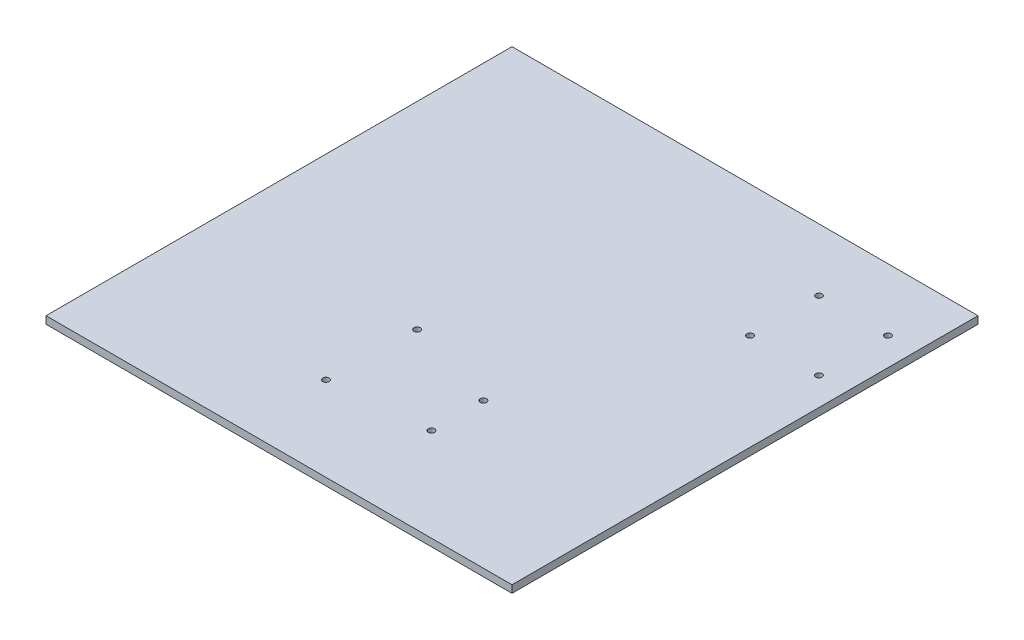
SolidWorks part; units mm, degrees
ref_plane "Front Plane" through (0, 0, 0) normal (0, 0, 1) x (1, 0, 0)
ref_plane "Top Plane" through (0, 0, 0) normal (0, 1, 0) x (1, 0, 0)
ref_plane "Right Plane" through (0, 0, 0) normal (1, 0, 0) x (0, 0, -1)
sketch "Sketch1" plane through (0, 0, 0) normal (0, 1, 0) x (1, 0, 0)
  line L1 (-124.1722, 92.3013) -> (125.8278, 92.3013)
  line L2 (-124.1722, 92.3013) -> (-124.1722, -157.6987)
  line L3 (-124.1722, -157.6987) -> (125.8278, -157.6987)
  line L4 (125.8278, 92.3013) -> (125.8278, -157.6987)
  dimension "D1" = 250
  dimension "D2" = 250
extrude "Boss-Extrude1" add sketch "Sketch1" along normal blind 4
sketch "Sketch3" plane through (0, 4, 0) normal (0, 1, 0) x (1, 0, 0)
  line L0 (-120.1722, -153.6987) -> (-120.1722, 88.3013) construction
  line L1 (-124.1722, 92.3013) -> (-120.1722, 92.3013) construction
  line L2 (-124.1722, 92.3013) -> (-124.1722, 88.3013) construction
  line L3 (-124.1722, 88.3013) -> (-120.1722, 88.3013) construction
  line L4 (-120.1722, 92.3013) -> (-120.1722, 88.3013) construction
  line L5 (-124.1722, 92.3013) -> (-120.1722, 88.3013) construction
  line L6 (-124.1722, 88.3013) -> (-120.1722, 92.3013) construction
  line L7 (-124.1722, -157.6987) -> (-120.1722, -157.6987) construction
  line L8 (-124.1722, -157.6987) -> (-124.1722, -153.6987) construction
  line L9 (-124.1722, -153.6987) -> (-120.1722, -153.6987) construction
  line L10 (-120.1722, -157.6987) -> (-120.1722, -153.6987) construction
  line L11 (-124.1722, -157.6987) -> (-120.1722, -153.6987) construction
  line L12 (-124.1722, -153.6987) -> (-120.1722, -157.6987) construction
  line L13 (-120.1722, -153.6987) -> (-124.1722, -153.6987) construction
  line L14 (-18.2122, -64.5887) -> (32.5878, -64.5887) construction
  line L15 (9.8278, 88.3013) -> (13.8278, 88.3013) construction
  line L16 (-120.1722, -19.6987) -> (-109.3111, -19.6987) construction
  line L17 (125.8278, -153.6987) -> (121.8278, -153.6987) construction
  line L18 (125.8278, -157.6987) -> (125.8278, 92.3013) construction
  line L19 (121.8278, -153.6987) -> (121.8278, -145.9665) construction
  line L20 (-33.4722, -115.3487) -> (35.1278, -115.3487) construction
  line L21 (-33.4722, -115.3487) -> (-33.4722, -62.0487) construction
  line L22 (-120.1722, -153.6987) -> (-120.1722, -23.6987) construction
  line L23 (-120.1722, -23.6987) -> (-77.34, -23.6987) construction
  line L24 (-33.4722, -62.0487) -> (35.1278, -62.0487) construction
  line L25 (35.1278, -115.3487) -> (35.1278, -62.0487) construction
  line L26 (-33.4722, -115.3487) -> (35.1278, -62.0487) construction
  line L27 (-33.4722, -62.0487) -> (35.1278, -115.3487) construction
  line L28 (32.5878, -64.5887) -> (32.5878, -79.7887) construction
  line L29 (32.5878, -79.7887) -> (32.5878, -107.6887) construction
  line L30 (32.5878, -107.6887) -> (32.5878, -112.3887) construction
  line L31 (32.5878, -112.3887) -> (-19.3122, -112.3887) construction
  line L32 (73.8871, 21.9371) -> (73.8871, 58.9371) construction
  line L33 (70.8871, 18.9371) -> (113.8871, 18.9371) construction
  line L34 (70.8871, 18.9371) -> (70.8871, 61.9371) construction
  line L35 (70.8871, 61.9371) -> (113.8871, 61.9371) construction
  line L36 (113.8871, 18.9371) -> (113.8871, 61.9371) construction
  line L37 (70.8871, 18.9371) -> (113.8871, 61.9371) construction
  line L38 (70.8871, 61.9371) -> (113.8871, 18.9371) construction
  line L39 (73.8871, 58.9371) -> (110.8871, 58.9371) construction
  line L40 (110.8871, 21.9371) -> (110.8871, 58.9371) construction
  line L41 (73.8871, 21.9371) -> (110.8871, 21.9371) construction
  circle A4 centre (-18.2122, -64.5887) radius 1.7
  circle A5 centre (-19.3122, -112.3887) radius 1.7
  circle A6 centre (32.5878, -79.7887) radius 1.7
  circle A7 centre (32.5878, -107.6887) radius 1.7
  circle A8 centre (73.8871, 21.9371) radius 1.7
  circle A9 centre (73.8871, 58.9371) radius 1.7
  circle A10 centre (110.8871, 21.9371) radius 1.7
  circle A11 centre (110.8871, 58.9371) radius 1.7
  point P4 (-122.1722, 90.3013)
  point P10 (-122.1722, -155.6987)
  point P30 (0.8278, -88.6987)
  point P49 (92.3871, 40.4371)
  dimension "D1" = 53.3
  dimension "D3" = 50.8
  dimension "D2" = 68.6
  dimension "D4" = 15.2
  dimension "D5" = 27.9
  dimension "D6" = 4.7
  dimension "D7" = 51.9
  dimension "D8" = 2.54
  dimension "D9" = 2.54
  dimension "D10" = 43
  dimension "D11" = 43
  dimension "D12" = 3
extrude "Cut-Extrude1" cut sketch "Sketch3" against normal blind 4
